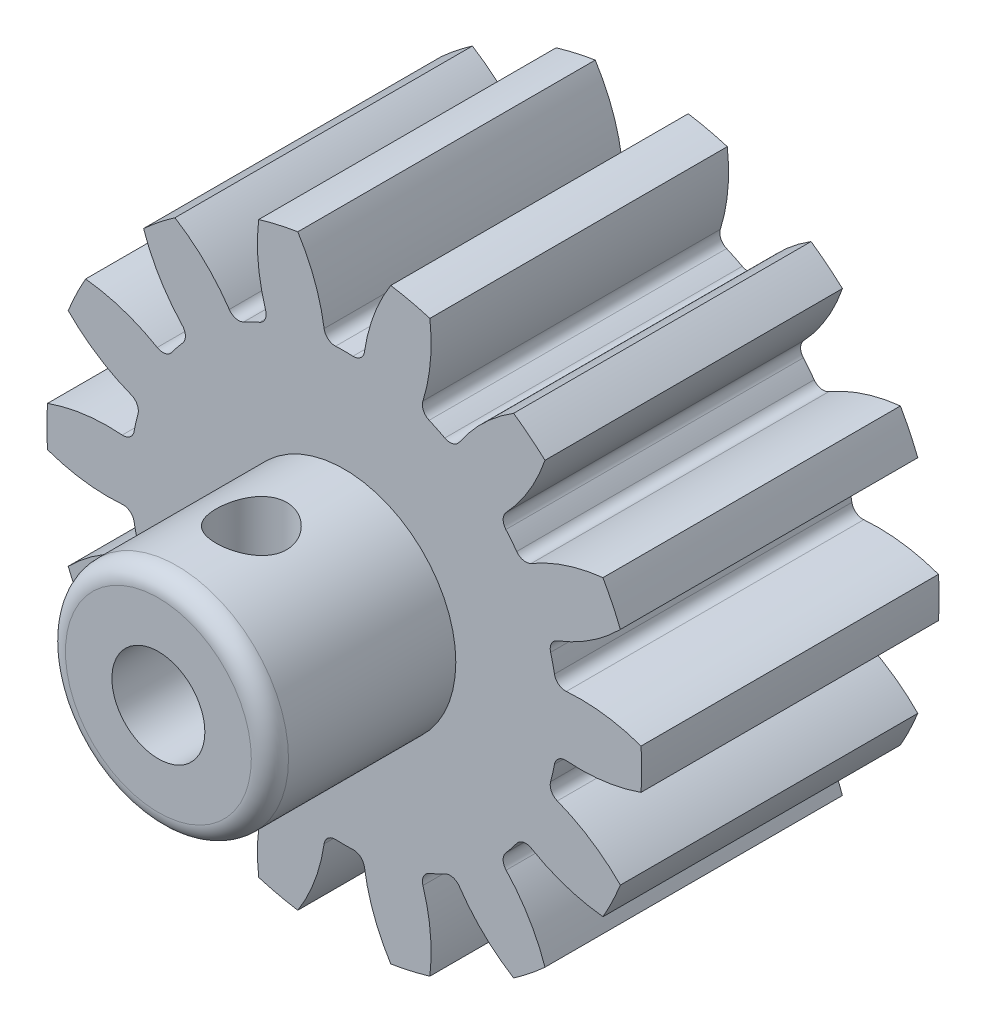
SolidWorks part; units mm, degrees
ref_plane "Ön Düzlem" through (0, 0, 0) normal (0, 0, 1) x (1, 0, 0)
ref_plane "Üst Düzlem" through (0, 0, 0) normal (0, 1, 0) x (1, 0, 0)
ref_plane "Sağ Düzlem" through (0, 0, 0) normal (1, 0, 0) x (0, 0, -1)
sketch "Çizim1" plane through (0, 0, 0) normal (0, 0, 1) x (1, 0, 0)
  circle A0 centre (0, 0) radius 14
  circle A1 centre (0, 0) radius 16
  circle A2 centre (0, 0) radius 11.5
  dimension "D1" = 28
  dimension "D2" = 32
  dimension "D3" = 23
extrude "Yükseklik-Ekstrüzyon1" add sketch "Çizim1" along normal mid plane 16 contours A1
sketch "Çizim2" plane through (0, 0, 8) normal (0, 0, 1) x (1, 0, 0)
  line L0 (0, 0) -> (0, 16) construction
  line L1 (-1.5675, 13.912) -> (1.5675, 13.912) construction
  line L2 (0, 9.6053) -> (-2.6177, 16.7973) construction
  line L3 (0, 0) -> (-1.0207, 11.4546) construction
  line L4 (0, 0) -> (3.5603, 15.5988) construction
  line L5 (1.5675, 13.912) -> (4.6239, 13.2144) construction
  circle A0 centre (0, 0) radius 16 construction
  arc A1 (-3.1496, 16.7057) -> (-1.0207, 11.4546) centre (-10.685, 10.5935) cw
  arc A2 (3.1496, 16.7057) -> (1.0207, 11.4546) centre (10.685, 10.5935) ccw
  circle A3 centre (0, 0) radius 11.5 construction
  arc A4 (1.0207, 11.4546) -> (-1.0207, 11.4546) centre (0, 0) ccw
  circle A5 centre (0, 0) radius 14 construction
  circle A6 centre (0, 0) radius 16 construction
  circle A7 centre (0, 0) radius 17
  arc A8 (3.1496, 16.7057) -> (-3.1496, 16.7057) centre (0, 0) ccw
  dimension "D2" = 20
  dimension "D3" = 12.857
  dimension "D1" = 1
extrude "Kes-Ekstrüzyon1" cut sketch "Çizim2" against normal blind 16
fillet "Radyus1" radius 0.6 2 edges at (1.0207, 11.4546, 0) (-1.0207, 11.4546, 0)
pattern_circular "Dairesel Kaplama1" count 14 over 360 about axis through (0, 0, 0) along (0, 0, 1) of "Radyus1", "Kes-Ekstrüzyon1"
sketch "Sketch1" plane through (0, 0, 8) normal (0, 0, 1) x (1, 0, 0)
  circle A0 centre (0, 0) radius 6
  circle A1 centre (0, 0) radius 2.5
  dimension "D1" = 12
  dimension "D2" = 5
extrude "Boss-Extrude1" add sketch "Sketch1" along normal blind 10
sketch "Sketch6" plane through (0, 0, 0) normal (0, 1, 0) x (1, 0, 0)
  line L0 (0, -18) -> (0, 0) construction
  line L1 (-6, -18) -> (6, -18) construction
  circle A0 centre (0, -13) radius 1.9
  dimension "D1" = 3.8
  dimension "D2" = 5
extrude "Cut-Extrude3" cut sketch "Sketch6" against normal through all both and the other way through all
fillet "Fillet1" radius 1 1 edges at (6, 0, 18)
sketch "Sketch7" plane through (0, 0, 18) normal (0, 0, 1) x (1, 0, 0)
  circle A0 centre (0, 0) radius 2.5
  dimension "D1" = 5
extrude "Cut-Extrude4" cut sketch "Sketch7" against normal blind 37
equation "\"m\"= 2mm'modül"
equation "\"z\"= 14'diş sayısı"
equation "\"D1@Çizim1\"=\"m\"*\"z\""
equation "\"D2@Çizim1\"=\"m\"*(\"z\"+2)"
equation "\"D3@Çizim1\"=\"m\"*(\"z\"-2.5)"
equation "\"D1@Yükseklik-Ekstrüzyon1\"=\"m\"*8"
equation "\"D3@Çizim2\"=180/\"z\""
equation "\"D1\"= \"m\" * 8"
equation "\"D1@Radyus1\"=\"m\"*0.3"
equation "\"D1@Dairesel Kaplama1\"=\"z\""
equation "\"D1@Kes-Ekstrüzyon1\"=\"m\"*8"
